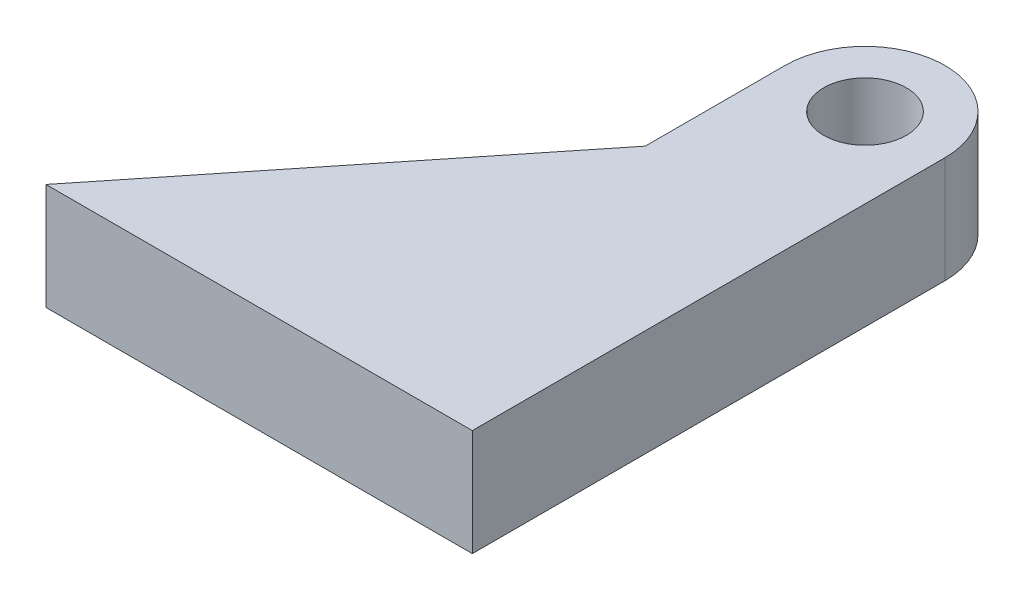
SolidWorks part; units mm, degrees
ref_plane "Front Plane" through (0, 0, 0) normal (0, 0, 1) x (1, 0, 0)
ref_plane "Top Plane" through (0, 0, 0) normal (0, 1, 0) x (1, 0, 0)
ref_plane "Right Plane" through (0, 0, 0) normal (1, 0, 0) x (0, 0, -1)
sketch "Sketch1" plane through (0, 0, 0) normal (0, 1, 0) x (1, 0, 0)
  line L1 (-15, 0) -> (-15.007, -26.2383)
  line L2 (-65.0017, -88.6925) -> (15, -88.6925)
  line L4 (-65.0017, -88.6925) -> (-15.007, -26.2383)
  line L6 (15, -88.6925) -> (15, 0)
  circle A0 centre (0, 0) radius 7.75
  arc A1 (15, 0) -> (-15, 0) centre (0, -0.004) ccw
  dimension "D1" = 15.5
  dimension "D3" = 80
extrude "Boss-Extrude1" add sketch "Sketch1" along normal blind 20
sketch "Sketch2" plane through (0, 20, 0) normal (0, 1, 0) x (1, 0, 0)
  line L0 (-65.0017, -88.6925) -> (15, -88.6925) construction
  line L1 (15, 0) -> (-15, 0)
  line L2 (15, 0) -> (15, -88.6925)
  line L3 (15, -88.6925) -> (-15, -88.6925)
  line L4 (-15, 0) -> (-15, -88.6925)
  dimension "D1" = 30
ref_point "Point1"
